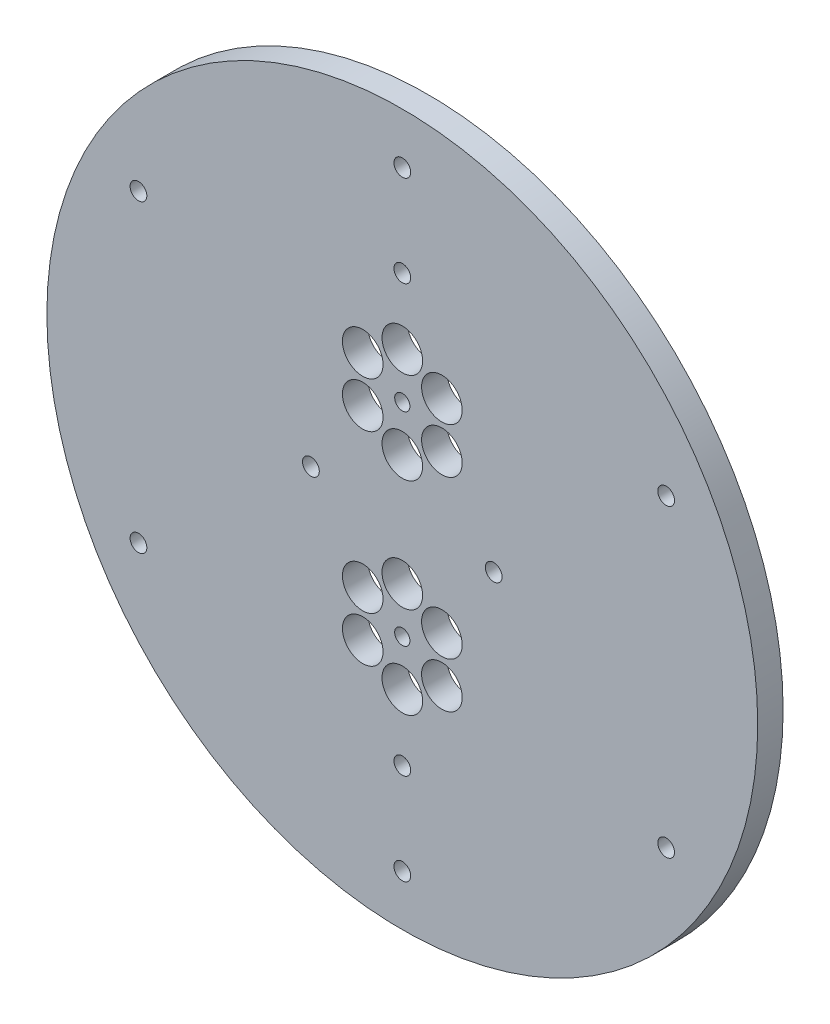
SolidWorks part; units mm, degrees
ref_plane "Front Plane" through (0, 0, 0) normal (0, 0, 1) x (1, 0, 0)
ref_plane "Top Plane" through (0, 0, 0) normal (0, 1, 0) x (1, 0, 0)
ref_plane "Right Plane" through (0, 0, 0) normal (1, 0, 0) x (0, 0, -1)
sketch "Sketch1" plane through (0, 0, 0) normal (0, 0, 1) x (1, 0, 0)
  line L0 (0, 70) -> (0, -70) construction
  line L1 (0, 0) -> (70, 0) construction
  circle A0 centre (0, 0) radius 70
  circle A2 centre (0, 0) radius 60 construction
  circle A3 centre (0, 60) radius 1.65
  circle A4 centre (51.9615, 30) radius 1.65
  circle A5 centre (51.9615, -30) radius 1.65
  circle A6 centre (0, -60) radius 1.65
  circle A7 centre (-51.9615, -30) radius 1.65
  circle A8 centre (-51.9615, 30) radius 1.65
  circle A9 centre (0, 0) radius 9 construction
  circle A10 centre (0, 0) radius 1.5 construction
  circle A11 centre (0, 9) radius 4 construction
  circle A12 centre (7.7942, 4.5) radius 4 construction
  circle A13 centre (7.7942, -4.5) radius 4 construction
  circle A14 centre (0, -9) radius 4 construction
  circle A15 centre (-7.7942, -4.5) radius 4 construction
  circle A16 centre (-7.7942, 4.5) radius 4 construction
  circle A17 centre (0, 20) radius 9 construction
  circle A18 centre (0, 29) radius 4
  circle A19 centre (7.7942, 24.5) radius 4
  circle A20 centre (7.7942, 15.5) radius 4
  circle A21 centre (0, 11) radius 4
  circle A22 centre (-7.7942, 15.5) radius 4
  circle A23 centre (-7.7942, 24.5) radius 4
  circle A24 centre (0, 20) radius 1.5
  circle A25 centre (7.7942, -15.5) radius 4
  circle A26 centre (0, -11) radius 4
  circle A27 centre (-7.7942, -15.5) radius 4
  circle A28 centre (0, -20) radius 1.5
  circle A29 centre (-7.7942, -24.5) radius 4
  circle A30 centre (0, -29) radius 4
  circle A31 centre (7.7942, -24.5) radius 4
  circle A32 centre (0, 0) radius 13 construction
  point P19 (0, 0)
  point P33 (0, 0)
  point P51 (0, 20)
  dimension "D1" = 140
  dimension "D2" = 18
  dimension "D3" = 10
  dimension "D4" = 3.3
  dimension "D6" = 6
  dimension "D7" = 8
  dimension "D8" = 3
  dimension "D9" = 18
  dimension "D12" = 26
  dimension "D10" = 20
  dimension "D5" = 6
  dimension "D11" = 6
extrude "Boss-Extrude1" add sketch "Sketch1" along normal blind 5
sketch "Sketch2" plane through (0, 0, 5) normal (0, 0, 1) x (1, 0, 0)
  line L0 (0, 0) -> (0, 37.6692) construction
  line L1 (0, 0) -> (16.9313, 0) construction
  circle A0 centre (0, 42) radius 1.65
  circle A1 centre (0, -42) radius 1.65
  circle A2 centre (18, 0) radius 1.65
  circle A3 centre (-18, 0) radius 1.65
  dimension "D1" = 3.3
  dimension "D2" = 36
  dimension "D3" = 84
extrude "Cut-Extrude1" cut sketch "Sketch2" against normal through all
